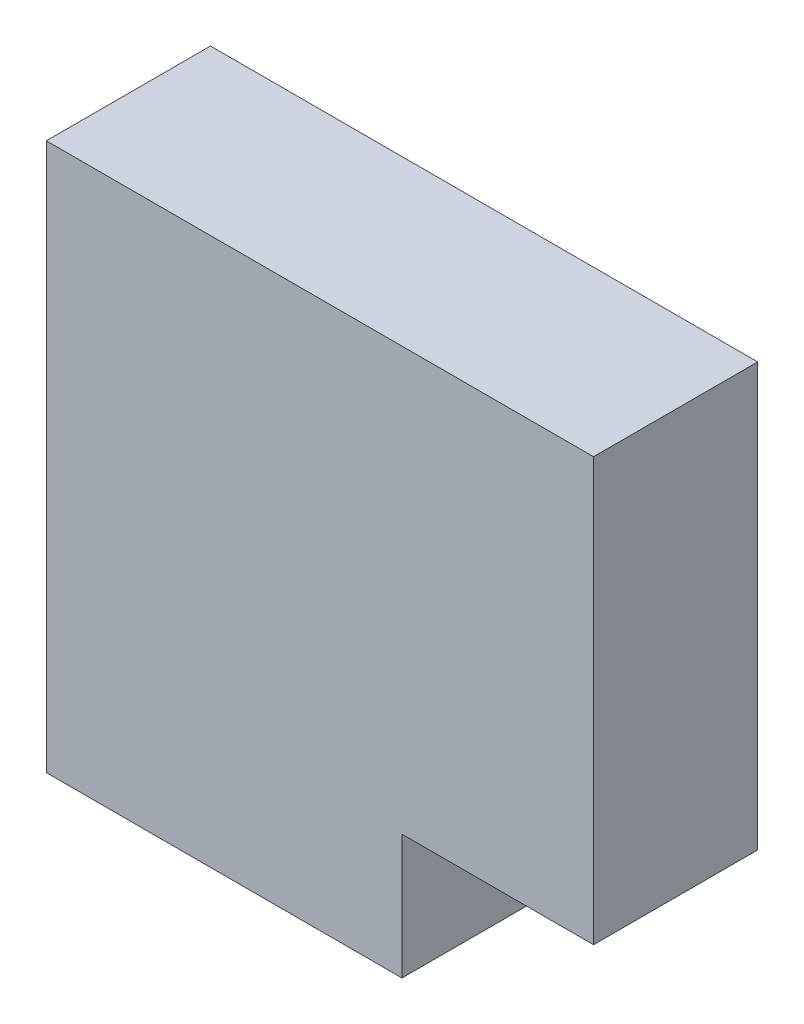
SolidWorks part; units mm, degrees
ref_plane "前基準面" through (0, 0, 0) normal (0, 0, 1) x (1, 0, 0)
ref_plane "上基準面" through (0, 0, 0) normal (0, 1, 0) x (1, 0, 0)
ref_plane "右基準面" through (0, 0, 0) normal (1, 0, 0) x (0, 0, -1)
sketch "草圖1" plane through (0, 0, 0) normal (0, 0, 1) x (1, 0, 0)
  line L1 (-7.7612, 11.0573) -> (12.2388, 11.0573)
  line L2 (-7.7612, 11.0573) -> (-7.7612, -8.9427)
  line L3 (-7.7612, -8.9427) -> (12.2388, -8.9427)
  line L4 (12.2388, 11.0573) -> (12.2388, -8.9427)
  dimension "D1" = 20
  dimension "D2" = 20
extrude "填料-伸長1" add sketch "草圖1" along normal blind 6
sketch "草圖2" plane through (0, 0, 6) normal (0, 0, 1) x (1, 0, 0)
  line L0 (-7.7612, -8.9427) -> (12.2388, -8.9427) construction
  line L1 (5.2388, -4.3905) -> (12.2388, -4.3905)
  line L2 (5.2388, -4.3905) -> (5.2388, -8.9427)
  line L3 (5.2388, -8.9427) -> (12.2388, -8.9427)
  line L4 (12.2388, -4.3905) -> (12.2388, -8.9427)
  line L6 (12.2388, -8.9427) -> (12.2388, 11.0573) construction
  dimension "D2" = 7
extrude "除料-伸長1" cut sketch "草圖2" against normal through all
